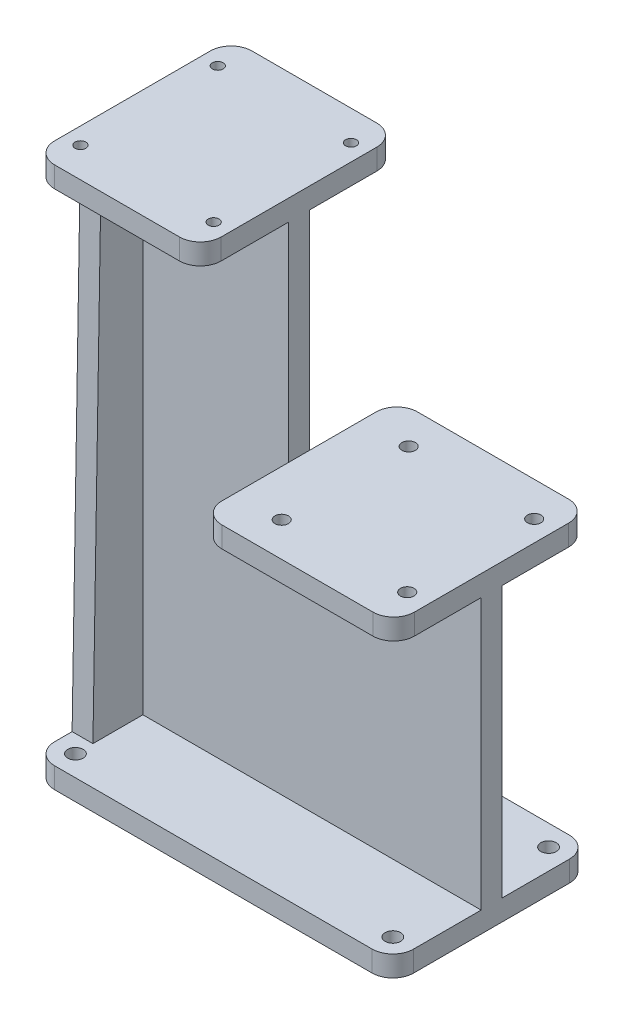
SolidWorks part; units mm, degrees
ref_plane "Front Plane" through (0, 0, 0) normal (0, 0, 1) x (1, 0, 0)
ref_plane "Top Plane" through (0, 0, 0) normal (0, 1, 0) x (1, 0, 0)
ref_plane "Right Plane" through (0, 0, 0) normal (1, 0, 0) x (0, 0, -1)
sketch "Skt - Base w mounting holes" plane through (0, 0, 0) normal (0, 1, 0) x (1, 0, 0)
  line L0 (-38.125, 23.7) -> (38.125, 23.7)
  line L1 (-38.125, -18.7) -> (38.125, -18.7) construction
  line L2 (-38.125, -18.7) -> (-38.125, 18.7) construction
  line L3 (-38.125, 18.7) -> (38.125, 18.7) construction
  line L4 (38.125, -18.7) -> (38.125, 18.7) construction
  line L5 (-38.125, -18.7) -> (38.125, 18.7) construction
  line L6 (-38.125, 18.7) -> (38.125, -18.7) construction
  line L7 (43.125, -18.7) -> (43.125, 18.7)
  line L8 (-38.125, -23.7) -> (38.125, -23.7)
  line L9 (-43.125, -18.7) -> (-43.125, 18.7)
  line L10 (-43.125, -23.7) -> (43.125, -23.7) construction
  line L11 (-43.125, -23.7) -> (-43.125, 23.7) construction
  line L12 (43.125, -23.7) -> (43.125, 23.7) construction
  line L13 (-43.125, 23.7) -> (43.125, 23.7) construction
  circle A0 centre (-38.125, 18.7) radius 1.85
  circle A1 centre (38.125, 18.7) radius 1.85
  circle A2 centre (38.125, -18.7) radius 1.85
  circle A3 centre (-38.125, -18.7) radius 1.85
  arc A4 (-38.125, -23.7) -> (-43.125, -18.7) centre (-38.125, -18.7) cw
  arc A5 (43.125, -18.7) -> (38.125, -23.7) centre (38.125, -18.7) cw
  arc A6 (38.125, 23.7) -> (43.125, 18.7) centre (38.125, 18.7) cw
  arc A7 (-38.125, 23.7) -> (-43.125, 18.7) centre (-38.125, 18.7) ccw
  point P0 (0, 0)
  dimension "D3" = 3.7
  dimension "D5" = 5
  dimension "D1" = 37.4
  dimension "D2" = 76.25
  dimension "D4" = 5
extrude "Ext - Base Plate w Mounting Holes" add sketch "Skt - Base w mounting holes" along normal blind 5 contours L8 A5 L7 A6 L0 A7 L9 A4
sketch "Skt - Upward Ridge" plane through (0, 5, 0) normal (0, 1, 0) x (1, 0, 0)
  line L0 (-43.125, 0) -> (43.125, 0) construction
  line L1 (-43.125, 18.7) -> (-43.125, -18.7) construction
  line L2 (43.125, -18.7) -> (43.125, 18.7) construction
  line L4 (-43.125, -2.5) -> (43.125, -2.5)
  line L5 (-43.125, -2.5) -> (-43.125, 2.5)
  line L6 (-43.125, 2.5) -> (43.125, 2.5)
  line L7 (43.125, -2.5) -> (43.125, 2.5)
  line L8 (-43.125, -2.5) -> (43.125, 2.5) construction
  line L9 (-43.125, 2.5) -> (43.125, -2.5) construction
  point P6 (0, 0)
  dimension "D1" = 5
extrude "Ext - Upward Flange" add sketch "Skt - Upward Ridge" along normal blind 65
sketch "Skt - GPS Nest" plane through (0, 70, 0) normal (0, 1, 0) x (1, 0, 0)
  line L0 (-43.125, 0) -> (43.125, 0) construction
  line L1 (-43.125, 2.5) -> (-43.125, -2.5) construction
  line L2 (43.125, -2.5) -> (43.125, 2.5) construction
  line L3 (43.125, -18.7) -> (43.125, -2.5) construction
  line L4 (1.875, 23.5) -> (38.125, 23.5)
  line L5 (-3.125, 18.5) -> (-3.125, -18.5)
  line L6 (1.875, -23.5) -> (38.125, -23.5)
  line L7 (43.125, 18.5) -> (43.125, -18.5)
  line L8 (-3.125, 23.5) -> (43.125, -23.5) construction
  line L9 (-3.125, -23.5) -> (43.125, 23.5) construction
  arc A0 (38.125, 23.5) -> (43.125, 18.5) centre (38.125, 18.5) cw
  arc A1 (-3.125, -18.5) -> (1.875, -23.5) centre (1.875, -18.5) ccw
  arc A2 (1.875, 23.5) -> (-3.125, 18.5) centre (1.875, 18.5) ccw
  arc A3 (38.125, -23.5) -> (43.125, -18.5) centre (38.125, -18.5) ccw
  point P6 (20, 0)
  dimension "D3" = 5
  dimension "D1" = 47
  dimension "D2" = 40
extrude "Ext - PIX Platform" add sketch "Skt - GPS Nest" along normal blind 5
sketch "Sketch7" plane through (0, 75, 0) normal (0, 1, 0) x (1, 0, 0)
  line L0 (-3.125, 0) -> (43.125, 0) construction
  line L1 (-3.125, 18.5) -> (-3.125, -18.5) construction
  line L2 (43.125, -18.5) -> (43.125, 18.5) construction
  line L3 (43.125, 0) -> (32.9734, 0) construction
  line L4 (7.975, -15.25) -> (38.125, -15.25) construction
  line L5 (7.975, -15.25) -> (7.975, 15.25) construction
  line L6 (38.125, -15.25) -> (38.125, 15.25) construction
  line L7 (7.975, 15.25) -> (38.125, 15.25) construction
  line L8 (7.975, -15.25) -> (38.125, 15.25) construction
  line L9 (38.125, -15.25) -> (7.975, 15.25) construction
  circle A0 centre (7.975, 15.25) radius 1.625
  circle A1 centre (38.125, 15.25) radius 1.625
  circle A2 centre (38.125, -15.25) radius 1.625
  circle A3 centre (7.975, -15.25) radius 1.625
  point P8 (23.05, 0)
  point P16 (0, 0)
  point P17 (43.125, 0)
  dimension "D4" = 3.25
  dimension "D1" = 30.5
  dimension "D2" = 5
  dimension "D3" = 30.15
extrude "Pix Mount Holes" cut sketch "Sketch7" against normal up to next
sketch "Sketch8" plane through (0, 70, 0) normal (0, 1, 0) x (1, 0, 0)
  line L1 (-43.125, 2.5) -> (-3.125, 2.5)
  line L2 (-43.125, 2.5) -> (-43.125, -2.5)
  line L3 (-43.125, -2.5) -> (-3.125, -2.5)
  line L4 (-3.125, 2.5) -> (-3.125, -2.5)
extrude "GPS Flange" add sketch "Sketch8" along normal blind 55
sketch "Sketch9" plane through (0, 125, 0) normal (0, 1, 0) x (1, 0, 0)
  line L0 (-43.125, 0) -> (-3.125, 0) construction
  line L1 (-43.125, 2.5) -> (-43.125, -2.5) construction
  line L2 (-3.125, -2.5) -> (-3.125, 2.5) construction
  line L3 (-38.125, -23.7) -> (38.125, -23.7) construction
  line L4 (-38.125, 23.7) -> (-8.125, 23.7)
  line L5 (-43.125, 18.7) -> (-43.125, -18.7)
  line L6 (-38.125, -23.7) -> (-8.125, -23.7)
  line L7 (-3.125, 18.7) -> (-3.125, -18.7)
  line L8 (-43.125, 23.7) -> (-3.125, -23.7) construction
  line L9 (-43.125, -23.7) -> (-3.125, 23.7) construction
  line L11 (-39.125, 16.5) -> (-7.125, 16.5) construction
  line L12 (-39.125, 16.5) -> (-39.125, -16.5) construction
  line L13 (-39.125, -16.5) -> (-7.125, -16.5) construction
  line L14 (-7.125, 16.5) -> (-7.125, -16.5) construction
  line L15 (-39.125, 16.5) -> (-7.125, -16.5) construction
  line L16 (-39.125, -16.5) -> (-7.125, 16.5) construction
  circle A0 centre (-39.125, 16.5) radius 1.3
  circle A1 centre (-7.125, 16.5) radius 1.3
  circle A2 centre (-7.125, -16.5) radius 1.3
  circle A3 centre (-39.125, -16.5) radius 1.3
  arc A4 (-43.125, 18.7) -> (-38.125, 23.7) centre (-38.125, 18.7) cw
  arc A5 (-3.125, -18.7) -> (-8.125, -23.7) centre (-8.125, -18.7) cw
  arc A6 (-3.125, 18.7) -> (-8.125, 23.7) centre (-8.125, 18.7) ccw
  arc A7 (-43.125, -18.7) -> (-38.125, -23.7) centre (-38.125, -18.7) ccw
  point P6 (-23.125, 0)
  point P13 (-23.125, 0)
  dimension "D3" = 2.6
  dimension "D4" = 5
  dimension "D1" = 32
  dimension "D2" = 33
extrude "GPS Platform" add sketch "Sketch9" along normal blind 5
sketch "Sketch10" plane through (-43.125, 0, 0) normal (-1, 0, 0) x (0, 0, 1)
  line L5 (0, 130) -> (0, 0) construction
  line L6 (-18.7, 130) -> (18.7, 130) construction
  line L10 (-18.7, 5) -> (-2.5, 5) construction
  line L11 (-2.5, 125) -> (-12.5, 125)
  line L12 (-2.5, 125) -> (-2.5, 5)
  line L13 (-2.5, 5) -> (-14.5, 5)
  line L14 (-12.5, 125) -> (-14.5, 5)
  line L16 (2.5, 5) -> (14.5, 5)
  line L17 (12.5, 125) -> (14.5, 5)
  line L18 (2.5, 125) -> (12.5, 125)
  line L19 (2.5, 125) -> (2.5, 5)
  line M13 (-18.7, 125) -> (-2.5, 125)
  line M14 (-2.5, 125) -> (-2.5, 5)
  line M15 (-2.5, 5) -> (-18.7, 5)
  dimension "D1" = 10
  dimension "D2" = 12
extrude "Bracing" add sketch "Sketch10" against normal blind 5 contours L14 M13 M15 M14
